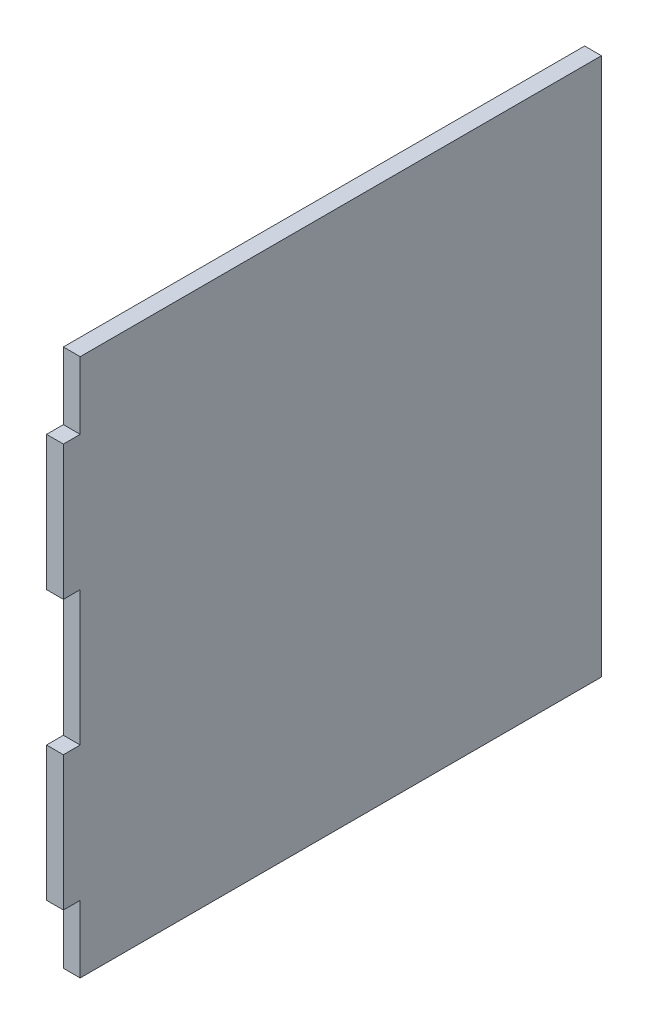
SolidWorks part; units mm, degrees
ref_plane "Front Plane" through (0, 0, 0) normal (0, 0, 1) x (1, 0, 0)
ref_plane "Top Plane" through (0, 0, 0) normal (0, 1, 0) x (1, 0, 0)
ref_plane "Right Plane" through (0, 0, 0) normal (1, 0, 0) x (0, 0, -1)
sketch "Sketch1" plane through (0, 0, 0) normal (1, 0, 0) x (0, 0, -1)
  line L1 (-80, 80) -> (80, 80)
  line L2 (-80, 80) -> (-80, -80)
  line L3 (-80, -80) -> (80, -80)
  line L4 (80, 80) -> (80, -80)
  line L5 (-80, 80) -> (80, -80) construction
  line L6 (-80, -80) -> (80, 80) construction
  point P0 (0, 0)
  dimension "D1" = 160
  dimension "D2" = 160
extrude "Boss-Extrude1" add sketch "Sketch1" along normal blind 5
sketch "Sketch2" plane through (5, 0, 0) normal (1, 0, 0) x (0, 0, -1)
  line L0 (-80, -60) -> (-75, -60)
  line L1 (-75, -60) -> (-75, -20)
  line L2 (-75, -20) -> (-80, -20)
  line L3 (-80, -20) -> (-80, 20)
  line L4 (-80, 20) -> (-75, 20)
  line L5 (-75, 20) -> (-75, 60)
  line L6 (-75, 60) -> (-80, 60)
  line L7 (-80, 60) -> (-80, -60)
  line L8 (-75, 20) -> (-75, -20)
  line L9 (0, 0) -> (75, 0) construction
  line L10 (80, 60) -> (75, 60)
  line L11 (75, 60) -> (75, 20)
  line L12 (75, 20) -> (80, 20)
  line L13 (80, 20) -> (80, -20)
  line L14 (80, -20) -> (75, -20)
  line L15 (75, -20) -> (75, -60)
  line L16 (75, -60) -> (80, -60)
  line L17 (80, -60) -> (80, 60)
  line L18 (75, 20) -> (75, -20)
  line L19 (0, 0) -> (-75, 0) construction
  line L20 (-80, 80) -> (-80, -80) construction
  line L21 (80, -80) -> (80, 80) construction
  line L22 (-75, 60) -> (-75, 80)
  line L23 (80, 80) -> (-80, 80) construction
  line L24 (-75, 80) -> (-80, 80)
  line L25 (-80, 80) -> (-80, 60)
  line L26 (-80, -60) -> (-80, -80)
  line L27 (-80, -80) -> (-75, -80)
  line L28 (-80, -80) -> (80, -80) construction
  line L29 (-75, -80) -> (-75, -60)
  line L30 (75, 60) -> (75, 80)
  line L31 (75, 80) -> (80, 80)
  line L32 (80, 80) -> (80, 60)
  line L33 (75, -60) -> (75, -80)
  line L34 (75, -80) -> (80, -80)
  line L35 (80, -80) -> (80, -60)
  line M7 (80, 80) -> (-80, 80)
  line M8 (-80, 80) -> (-80, -80)
  line M9 (-80, -80) -> (80, -80)
  dimension "D1" = 40
  dimension "D2" = 40
  dimension "D3" = 5
  dimension "D4" = 40
  dimension "D5" = 5
  dimension "D6" = 40
extrude "Cut-Extrude1" cut sketch "Sketch2" against normal through all contours L6 L22 M7 M8 | L8 L4 L2 M8 | L29 L0 M9 M8
